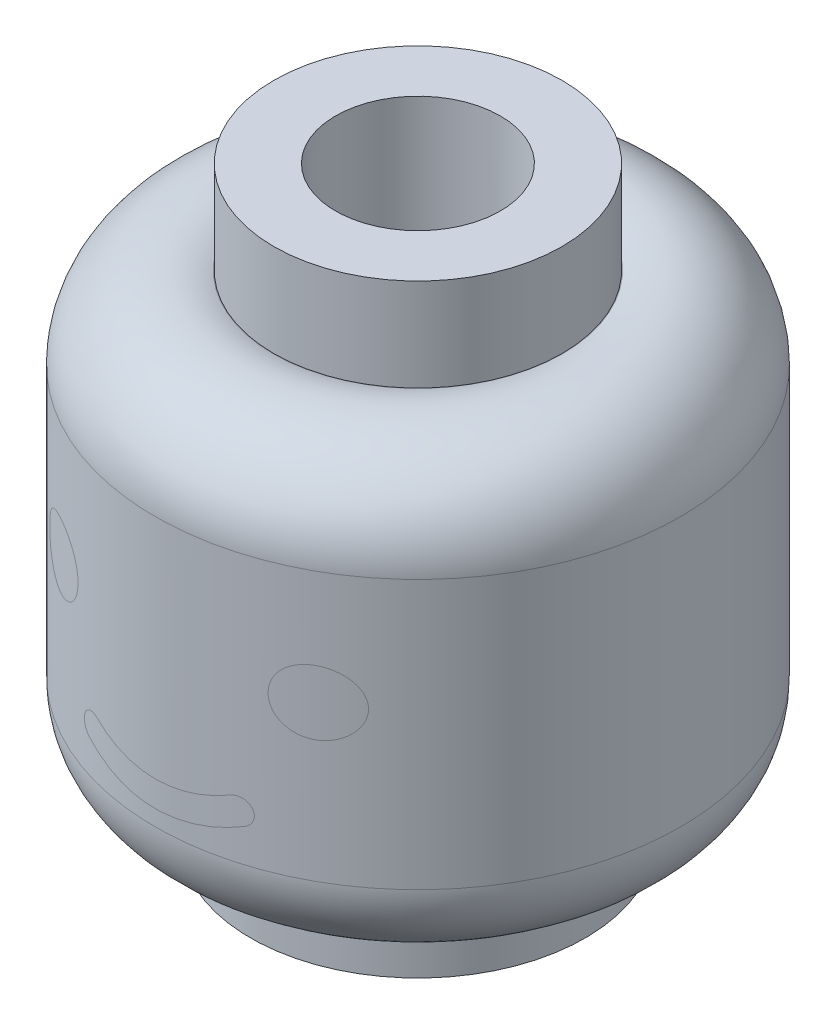
SolidWorks part; units mm, degrees
ref_plane "Front Plane" through (0, 0, 0) normal (0, 0, 1) x (1, 0, 0)
ref_plane "Top Plane" through (0, 0, 0) normal (0, 1, 0) x (1, 0, 0)
ref_plane "Right Plane" through (0, 0, 0) normal (1, 0, 0) x (0, 0, -1)
sketch "Sketch1" plane through (0, 0, 0) normal (0, 0, 1) x (1, 0, 0)
  line L0 (0, 0) -> (0, 11.5086) construction
  line L1 (0, 8.8615) -> (0, 9.7615)
  line L2 (0, 9.7615) -> (1.6, 9.7615)
  line L3 (1.6, 9.7615) -> (1.6, 11.7615)
  line L4 (1.6, 11.7615) -> (2.7969, 11.7615)
  line L5 (2.7969, 11.7615) -> (2.7969, 9.9615)
  line L6 (2.7969, 9.9615) -> (2.8099, 9.9663)
  line L7 (5.1, 8.372) -> (5.1, 3.155)
  line L8 (3.2736, 1.4597) -> (3.25, 1.4615)
  line L9 (3.25, 1.4615) -> (3.25, 0.3615)
  line L10 (3.25, 0.3615) -> (2.45, 0.3615)
  line L11 (2.45, 0.3615) -> (2.45, 8.8615)
  line L12 (2.45, 8.8615) -> (0, 8.8615)
  arc A0 (3.2736, 1.4597) -> (5.1, 3.155) centre (3.4, 3.155) ccw
  arc A1 (2.8099, 9.9663) -> (5.1, 8.372) centre (3.4, 8.372) cw
  point P21 (5.1, 1.3235)
  point P26 (5.1, 5.7635)
  dimension "D9" = 1.7
  dimension "D1" = 2.45
  dimension "D2" = 2.65
  dimension "D3" = 0.8
  dimension "D4" = 1.1
  dimension "D5" = 1.8
  dimension "D6" = 2
  dimension "D7" = 2.9
  dimension "D8" = 1.6
  dimension "D10" = 9.6
revolve "Head Revolve" add sketch "Sketch1" angle 360 about L0
sketch "Sketch2" plane through (0, 9.7615, 0) normal (0, 1, 0) x (1, 0, 0)
  line L0 (0, 1.6) -> (0, 0) construction
  line L1 (0, 0) -> (-1.3856, -0.8) construction
  line L2 (-0.42, 1.5439) -> (-0.42, 0.2425)
  line L3 (-0.42, 0.2425) -> (-1.547, -0.4082)
  line L4 (-0.42, 1.6) -> (-0.42, 0.2425) construction
  line L5 (-0.42, 0.2425) -> (-1.5956, -0.4363) construction
  circle A0 centre (0, 0) radius 1.6 construction
  circle A1 centre (0, 0) radius 1.6 construction
  arc A2 (-1.3856, -0.8) -> (0, 1.6) centre (0, 0) ccw
  circle A3 centre (0, 0) radius 1.6
  arc A4 (-0.42, 1.5439) -> (-1.547, -0.4082) centre (0, 0) ccw
  circle M4 centre (0, 0) radius 1.6
  dimension "D1" = 120
  dimension "D2" = 0.42
  dimension "D3" = 0
extrude "Cut-Extrude1" cut sketch "Sketch2" against normal blind 10 contours L3 L2 M4
pattern_circular "CirPattern1" count 3 over 360 about axis through (0, 0, 0) along (0, 1, 0) of "Cut-Extrude1"
sketch "Sketch3" plane through (0, 0, 0) normal (0, 0, 1) x (1, 0, 0)
  line L0 (0, 11.7615) -> (0, 0.3615) construction
  line L1 (1.6, 11.7615) -> (-1.6, 11.7615) construction
  line L2 (-3.25, 0.3615) -> (3.25, 0.3615) construction
  line L3 (-5.1, 6.1615) -> (5.1, 6.1615) construction
  line L4 (-5.1, 8.372) -> (-5.1, 3.155) construction
  line L5 (5.1, 3.155) -> (5.1, 8.372) construction
  line L6 (-5.1, 3.4615) -> (5.1, 3.4615) construction
  circle A0 centre (-2.47, 6.1615) radius 0.625
  circle A1 centre (2.47, 6.1615) radius 0.625
  arc A2 (1.4, 4.0285) -> (-1.4, 4.0285) centre (0, 6.9615) cw construction
  arc A15 (-1.5077, 3.8029) -> (1.5077, 3.8029) centre (0, 6.9615) ccw
  arc A16 (-1.2923, 4.2541) -> (1.2923, 4.2541) centre (0, 6.9615) ccw
  arc A17 (-1.2923, 4.2541) -> (-1.5077, 3.8029) centre (-1.4, 4.0285) ccw
  arc A18 (1.5077, 3.8029) -> (1.2923, 4.2541) centre (1.4, 4.0285) ccw
  point P21 (-18.7048, 9.6299)
  point P23 (0, 3.7115)
  point P28 (2.1304, 3.155)
  point P29 (-2.0878, 3.4615)
  point P30 (-0.8035, 3.1735)
  point P31 (1.2569, 3.155)
  point P32 (-18.5557, 7.6273)
  dimension "D3" = 1.25
  dimension "D5" = 0.25
  dimension "D7" = 3.5
  dimension "D1" = 3.1
  dimension "D2" = 5.6
  dimension "D4" = 4.94
  dimension "D6" = 2.8
split line "Split Line1"
